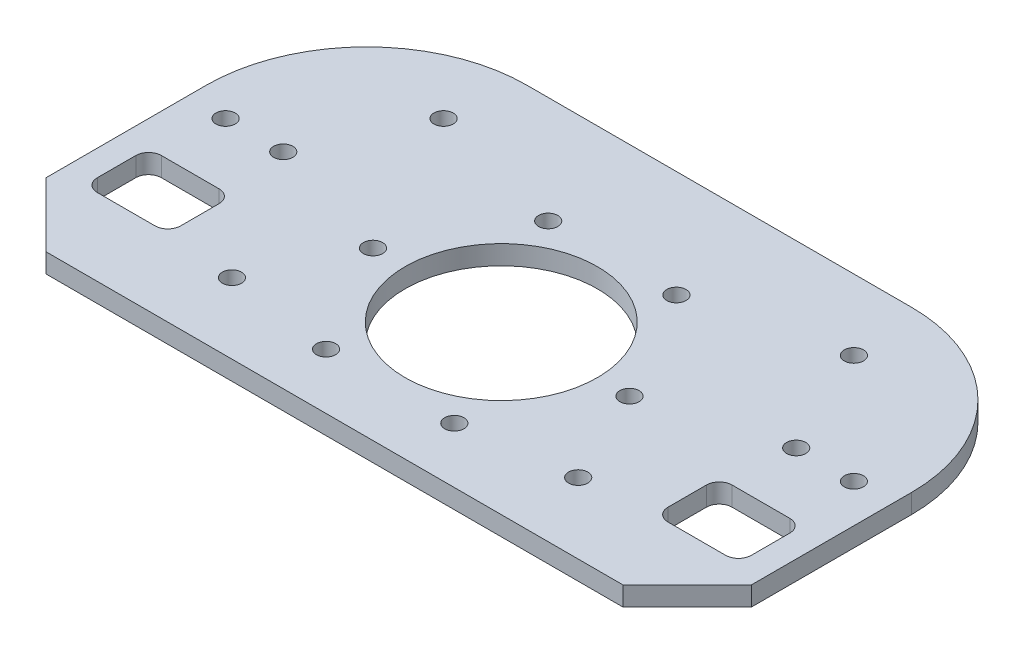
SolidWorks part; units mm, degrees
material "Thornel Mat VMA"
ref_plane "前视基准面" through (0, 0, 0) normal (0, 0, 1) x (1, 0, 0)
ref_plane "上视基准面" through (0, 0, 0) normal (0, 1, 0) x (1, 0, 0)
ref_plane "右视基准面" through (0, 0, 0) normal (1, 0, 0) x (0, 0, -1)
other "Configuration Table"
sketch "草图1" plane through (0, 0, 0) normal (0, 1, 0) x (1, 0, 0)
  line L0 (0, 0) -> (0, 30) construction
  line L1 (-55, -30) -> (55, -30)
  line L2 (-55, -30) -> (-55, 30)
  line L3 (-55, 30) -> (55, 30)
  line L4 (55, -30) -> (55, 30)
  line L5 (-55, -30) -> (55, 30) construction
  line L6 (-55, 30) -> (55, -30) construction
  line L7 (-66.4906, 0) -> (66.4906, 0) construction
  circle A0 centre (-49, 2) radius 1.5
  circle A1 centre (-40, 2) radius 1.5
  circle A2 centre (49, 2) radius 1.5
  circle A3 centre (40, 2) radius 1.5
  point P0 (0, 0)
  point P19 (0, 0)
  dimension "D3" = 3
  dimension "D4" = 3
  dimension "D1" = 110
  dimension "D2" = 60
  dimension "D5" = 9
  dimension "D6" = 98
  dimension "D7" = 2
  dimension "D8" = 2
extrude "凸台-拉伸1" add sketch "草图1" along normal blind 3
fillet "圆角1" radius 25 2 edges at (55, 1.5, -30) (-55, 1.5, -30)
chamfer "倒角1" distance 10 angle 45 2 edges at (55, 1.5, 30) (-55, 1.5, 30)
sketch "草图3" plane through (0, 3, 0) normal (0, 1, 0) x (1, 0, 0)
  line L0 (0, 0) -> (0, 37.1437) construction
  line L1 (0, 0) -> (65.1008, 0) construction
  circle A0 centre (-32, 19) radius 1.5
  circle A1 centre (-27, -19) radius 1.5
  circle A3 centre (27, -19) radius 1.5
  circle A4 centre (32, 19) radius 1.5
  dimension "D1" = 3
  dimension "D2" = 32
  dimension "D5" = 3
  dimension "D3" = 19
  dimension "D4" = 19
  dimension "D6" = 27
extrude "切除-拉伸2" cut sketch "草图3" against normal blind 3
sketch "草图4" plane through (0, 3, 0) normal (0, 1, 0) x (1, 0, 0)
  line L0 (0, 0) -> (0, 35.5537) construction
  line L1 (-51, -18) -> (-38, -18)
  line L2 (-51, -18) -> (-51, -8)
  line L3 (-51, -8) -> (-38, -8)
  line L4 (-38, -18) -> (-38, -8)
  line L5 (-51, -18) -> (-38, -8) construction
  line L6 (-51, -8) -> (-38, -18) construction
  line L7 (0, 0) -> (62.0092, 0) construction
  line L8 (51, -8) -> (38, -8)
  line L9 (38, -18) -> (38, -8)
  line L10 (51, -18) -> (38, -18)
  line L11 (51, -18) -> (51, -8)
  point P0 (-44.5, -13)
  dimension "D1" = 13
  dimension "D2" = 10
  dimension "D3" = 38
  dimension "D4" = 8
extrude "切除-拉伸3" cut sketch "草图4" against normal blind 10
fillet "圆角2" radius 2 8 edges at (51, 1.5, 8) (51, 1.5, 18) (38, 1.5, 18) (38, 1.5, 8) (-51, 1.5, 18) (-38, 1.5, 18) (-51, 1.5, 8) (-38, 1.5, 8)
sketch "草图5" plane through (0, 3, 0) normal (0, 1, 0) x (1, 0, 0)
  line L0 (0, 0) -> (0, 38.7336) construction
  line L1 (0, 0) -> (61.7442, 0) construction
  line L2 (0, 0) -> (0, -36.0837) construction
  line L3 (-30.2096, -4) -> (30.2096, -4) construction
  line L4 (0, -4) -> (15.0261, 22.026) construction
  circle A1 centre (20, -4) radius 1.5
  circle A2 centre (10, 13.3205) radius 1.5
  circle A3 centre (-20, -4) radius 1.5
  circle A4 centre (-10, 13.3205) radius 1.5
  circle A5 centre (10, -21.3205) radius 1.5
  circle A6 centre (-10, -21.3205) radius 1.5
  circle A7 centre (0, -4) radius 15
  point P8 (0, -4)
  dimension "D2" = 3
  dimension "D4" = 20
  dimension "D5" = 3
  dimension "D7" = 30
  dimension "D1" = 4
  dimension "D3" = 60
  dimension "D6" = 20
extrude "切除-拉伸4" cut sketch "草图5" against normal blind 3
